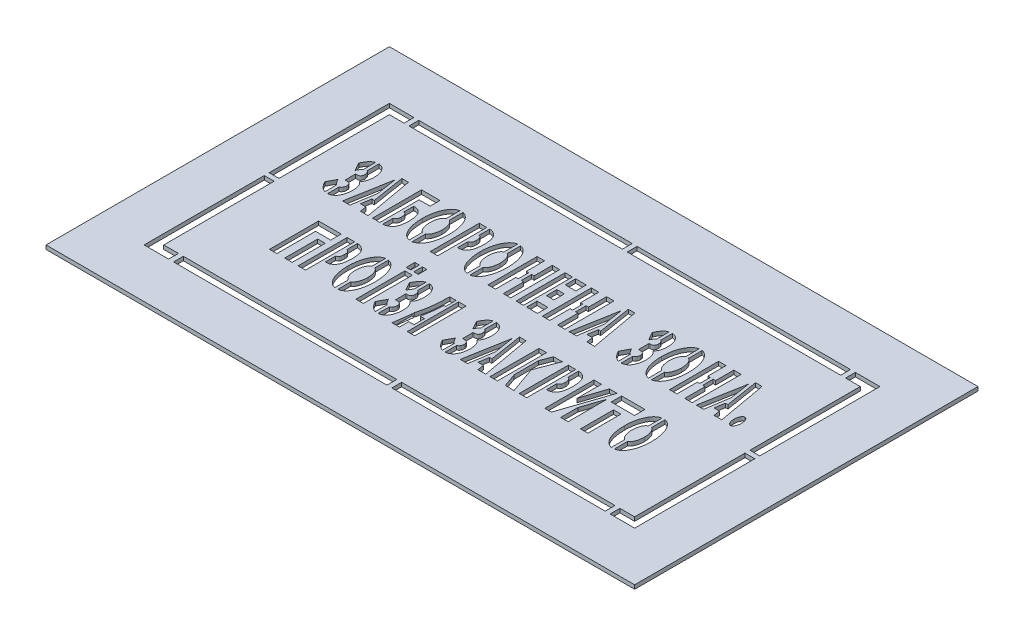
SolidWorks part; units mm, degrees
ref_plane "Спереди" through (0, 0, 0) normal (0, 0, 1) x (1, 0, 0)
ref_plane "Сверху" through (0, 0, 0) normal (0, 1, 0) x (1, 0, 0)
ref_plane "Справа" through (0, 0, 0) normal (1, 0, 0) x (0, 0, -1)
sketch "Эскиз1" plane through (0, 0, 0) normal (0, 1, 0) x (1, 0, 0)
  line L0 (25, 250) -> (25, 240)
  line L1 (0, 250) -> (500, 250)
  line L2 (0, 250) -> (0, 0)
  line L3 (0, 0) -> (500, 0)
  line L4 (500, 250) -> (500, 0)
  line L5 (30, 250) -> (30, 240)
  line L6 (0, 125) -> (-49.6951, 125) construction
  line L7 (10, 240) -> (490, 240)
  line L8 (10, 240) -> (10, 10)
  line L9 (10, 10) -> (490, 10)
  line L10 (490, 240) -> (490, 10)
  line L11 (250, 250) -> (250, 284.0129) construction
  line L12 (470, 250) -> (470, 240)
  line L13 (475, 250) -> (475, 240)
  line L14 (247.5, 250) -> (247.5, 240)
  line L15 (252.5, 250) -> (252.5, 240)
  line L16 (475, 0) -> (475, 10)
  line L17 (470, 0) -> (470, 10)
  line L18 (30, 0) -> (30, 10)
  line L19 (25, 0) -> (25, 10)
  line L20 (252.5, 0) -> (252.5, 10)
  line L21 (247.5, 0) -> (247.5, 10)
  line L22 (0, 127.5) -> (10, 127.5)
  line L23 (0, 122.5) -> (10, 122.5)
  line L24 (500, 122.5) -> (490, 122.5)
  line L25 (500, 127.5) -> (490, 127.5)
  line L27 (-50, -50) -> (550, -50)
  line L28 (-50, -50) -> (-50, 300)
  line L29 (-50, 300) -> (550, 300)
  line L30 (550, -50) -> (550, 300)
  point P0 (0, 0)
  point P6 (0, 0)
  dimension "D1" = 500
  dimension "D2" = 250
  dimension "D3" = 10
  dimension "D4" = 10
  dimension "D5" = 10
  dimension "D6" = 10
  dimension "D7" = 5
  dimension "D8" = 15
  dimension "D9" = 5
  dimension "D10" = 5
  dimension "D11" = 600
  dimension "D12" = 350
  dimension "D13" = 50
  dimension "D14" = 50
extrude "Бобышка-Вытянуть1" add sketch "Эскиз1" along normal blind 4 contours L10 L7 L8 L9 | L19 L3 L18 L9 | L21 L3 L20 L9 | L17 L3 L16 L9 | L4 L25 L10 L24 | L13 L1 L12 L7 | L15 L1 L14 L7 | L0 L7 L5 L1 | L2 L23 L8 L22 | L27 L30 L29 L28 L1 L4 L3 L2
sketch "Эскиз2" plane through (0, 4, 0) normal (0, 1, 0) x (1, 0, 0)
  line L0 (14.7357, 140) -> (485.2643, 140) construction
  line L2 (250, 140) -> (250, 300) construction
  line L3 (-50, 300) -> (550, 300) construction
  line L4 (14.7357, 60) -> (485.2643, 60) construction
  line L5 (485.2643, 60) -> (485.2643, 140) construction
  line L6 (14.7357, 140) -> (14.7357, 60) construction
  line L7 (-50, 125) -> (-122.4254, 125) construction
  line L8 (-50, -50) -> (-50, 300) construction
  line L12 (0, 0) -> (25, 0) construction
  text T0 "ЗАБОРОНЕНА ЗОНА." font "Sargento Gorila" height 50
  text T1 "ПРОЇЗД ЗАКРИТО" font "Sargento Gorila" height 50
  dimension "D1" = 15
  dimension "D2" = 65
  dimension "D3" = 60
extrude "Вырез-Вытянуть1" cut sketch "Эскиз2" against normal blind 4
